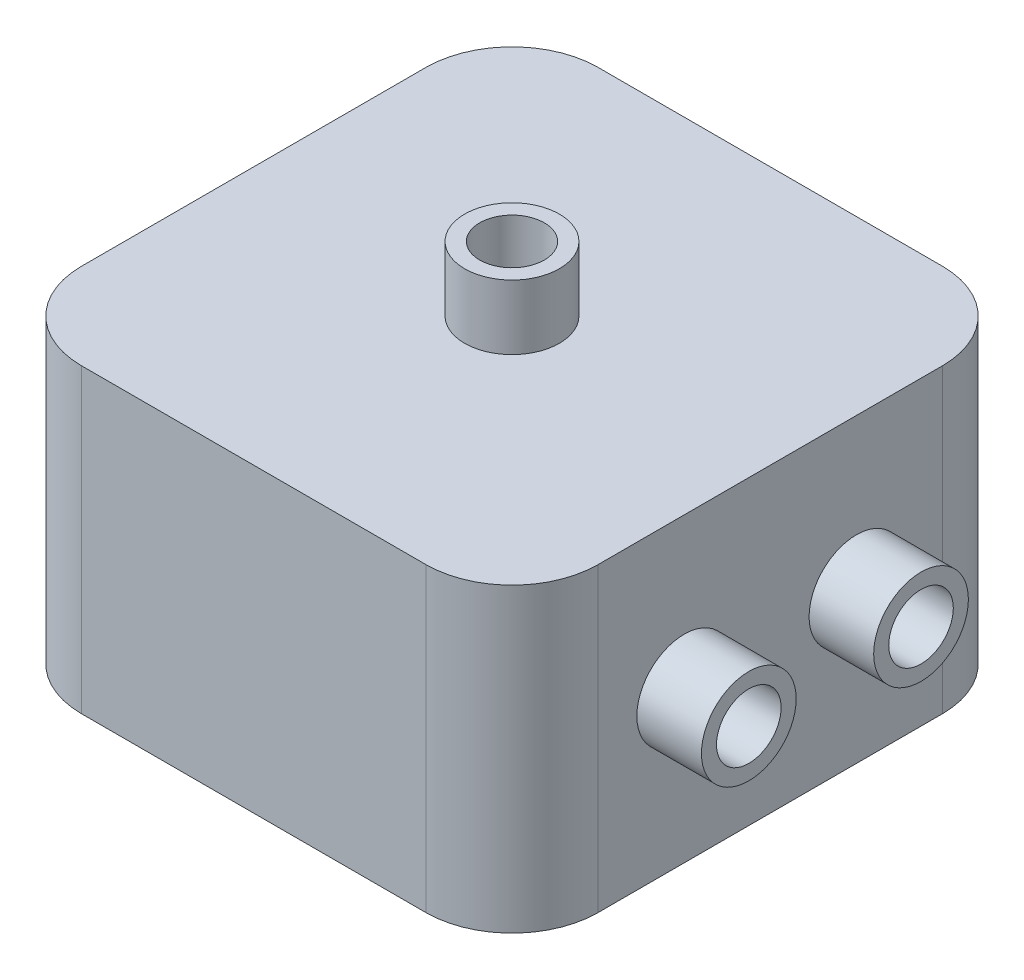
SolidWorks part; units mm, degrees
other "Câmera1"
material "PET"
ref_plane "Plano frontal" through (0, 0, 0) normal (0, 0, 1) x (1, 0, 0)
ref_plane "Plano superior" through (0, 0, 0) normal (0, 1, 0) x (1, 0, 0)
ref_plane "Plano direito" through (0, 0, 0) normal (1, 0, 0) x (0, 0, -1)
sketch "Esboço1" plane through (0, 0, 0) normal (0, 1, 0) x (1, 0, 0)
  line L0 (40, 60) -> (-40, 60)
  line L1 (40, -50) -> (-40, -50)
  line L2 (50, -40) -> (50, 40)
  line L3 (40, 50) -> (-40, 50)
  line L4 (-50, -40) -> (-50, 40)
  line L5 (50, -50) -> (-50, 50) construction
  line L6 (50, 50) -> (-50, -50) construction
  line L7 (-60, -40) -> (-60, 40)
  line L8 (40, -60) -> (-40, -60)
  line L9 (60, -40) -> (60, 40)
  arc A0 (-40, -50) -> (-50, -40) centre (-40, -40) cw
  arc A1 (50, -40) -> (40, -50) centre (40, -40) cw
  arc A2 (50, 40) -> (40, 50) centre (40, 40) ccw
  arc A3 (-40, 50) -> (-50, 40) centre (-40, 40) ccw
  arc A4 (-40, 60) -> (-60, 40) centre (-40, 40) ccw
  arc A5 (-40, -60) -> (-60, -40) centre (-40, -40) cw
  arc A6 (60, -40) -> (40, -60) centre (40, -40) cw
  arc A7 (60, 40) -> (40, 60) centre (40, 40) ccw
  point P0 (0, 0)
  dimension "D3" = 10
  dimension "D1" = 100
  dimension "D2" = 100
  dimension "D4" = 10
extrude "Ressalto-extrusão1" add sketch "Esboço1" along normal blind 50
ref_plane "Plano1" through (0, 50, 0) normal (0, 1, 0) x (1, 0, 0)
sketch "Esboço2" plane through (0, 50, 0) normal (0, 1, 0) x (1, 0, 0)
  line L0 (-40, -50) -> (40, -50) construction
  line L1 (-40, 50) -> (40, 50) construction
  line L2 (-50, 40) -> (-50, -40) construction
  line L3 (-40, -50) -> (40, -50) construction
  line L4 (50, 40) -> (50, -40) construction
  line L5 (-50, 50) -> (50, -50) construction
  line L6 (-50, -50) -> (50, 50) construction
  line L7 (50, -40) -> (50, 40) construction
  line L8 (-40, -60) -> (40, -60)
  line L9 (60, 40) -> (60, -40)
  line L10 (-40, 60) -> (40, 60)
  line L11 (-60, 40) -> (-60, -40)
  arc A0 (-50, -40) -> (-40, -50) centre (-40, -40) ccw construction
  arc A1 (40, 50) -> (50, 40) centre (40, 40) cw construction
  arc A2 (-40, 50) -> (-50, 40) centre (-40, 40) ccw construction
  arc A3 (40, -50) -> (50, -40) centre (40, -40) ccw construction
  arc A4 (40, -60) -> (60, -40) centre (40, -40) ccw
  arc A5 (40, 60) -> (60, 40) centre (40, 40) cw
  arc A6 (-40, 60) -> (-60, 40) centre (-40, 40) ccw
  arc A7 (-60, -40) -> (-40, -60) centre (-40, -40) ccw
  point P0 (0, 0)
  dimension "D1" = 10
  dimension "D2" = 10
extrude "Ressalto-extrusão2" add sketch "Esboço2" along normal blind 10
ref_plane "Plano2" through (0, 0, 0) normal (0, -1, 0) x (-1, 0, 0)
sketch "Esboço3" plane through (0, 0, 0) normal (0, -1, 0) x (-1, 0, 0)
  line L0 (40, -50) -> (-40, -50) construction
  line L1 (40, 50) -> (-40, 50) construction
  line L2 (50, 40) -> (50, -40) construction
  line L3 (40, -50) -> (-40, -50) construction
  line L4 (-50, 40) -> (-50, -40) construction
  line L5 (50, 50) -> (-50, -50) construction
  line L6 (50, -50) -> (-50, 50) construction
  line L7 (-50, -40) -> (-50, 40) construction
  line L8 (40, -60) -> (-40, -60)
  line L9 (-60, 40) -> (-60, -40)
  line L10 (40, 60) -> (-40, 60)
  line L11 (60, 40) -> (60, -40)
  arc A0 (-50, -40) -> (-40, -50) centre (-40, -40) ccw construction
  arc A1 (-40, 50) -> (-50, 40) centre (-40, 40) ccw construction
  arc A2 (50, 40) -> (40, 50) centre (40, 40) ccw construction
  arc A3 (40, -50) -> (50, -40) centre (40, -40) ccw construction
  arc A4 (-60, -40) -> (-40, -60) centre (-40, -40) ccw
  arc A5 (-40, 60) -> (-60, 40) centre (-40, 40) ccw
  arc A6 (60, 40) -> (40, 60) centre (40, 40) ccw
  arc A7 (40, -60) -> (60, -40) centre (40, -40) ccw
  point P0 (0, 0)
  dimension "D1" = 10
  dimension "D2" = 10
extrude "Ressalto-extrusão3" add sketch "Esboço3" along normal blind 10
ref_plane "Plano3" through (-60, 0, 0) normal (-1, 0, 0) x (0, 0, 1)
sketch "Esboço4" plane through (-60, 0, 0) normal (-1, 0, 0) x (0, 0, 1)
  line L0 (0, 60) -> (0, -10) construction
  line L1 (-40, 60) -> (40, 60) construction
  line L2 (40, -10) -> (-40, -10) construction
  line L3 (-40, 25) -> (40, 25) construction
  line L4 (-40, 60) -> (-40, -10) construction
  line L5 (40, 60) -> (40, -10) construction
  line L6 (0, 25) -> (40, 25) construction
  circle A0 centre (20, 25) radius 11
  circle A1 centre (-20, 25) radius 11
extrude "Ressalto-extrusão4" add sketch "Esboço4" along normal blind 15
ref_plane "Plano4" through (60, 0, 0) normal (1, 0, 0) x (0, 0, -1)
sketch "Esboço5" plane through (60, 0, 0) normal (1, 0, 0) x (0, 0, -1)
  line L0 (0, 0) -> (0, 60) construction
  line L1 (-40, 60) -> (40, 60) construction
  line L2 (40, 25) -> (0, 25) construction
  line L3 (40, 60) -> (40, -10) construction
  line L4 (0, 25) -> (-40, 25) construction
  line L5 (-40, 60) -> (-40, -10) construction
  circle A0 centre (-20, 25) radius 11
  circle A1 centre (20, 25) radius 11
extrude "Ressalto-extrusão5" add sketch "Esboço5" along normal blind 15
ref_plane "Plano5" through (-75, 0, 0) normal (-1, 0, 0) x (0, 0, 1)
sketch "Esboço6" plane through (-75, 0, 0) normal (-1, 0, 0) x (0, 0, 1)
  circle A0 centre (20, 25) radius 7.5
  circle A1 centre (-20, 25) radius 7.5
extrude "Corte-extrusão1" cut sketch "Esboço6" against normal blind 200
ref_plane "Plano6" through (0, 60, 0) normal (0, 1, 0) x (1, 0, 0)
sketch "Esboço7" plane through (0, 60, 0) normal (0, 1, 0) x (1, 0, 0)
  circle A0 centre (0, 0) radius 11
extrude "Ressalto-extrusão6" add sketch "Esboço7" along normal blind 15
ref_plane "Plano7" through (0, 75, 0) normal (0, 1, 0) x (1, 0, 0)
sketch "Esboço8" plane through (0, 75, 0) normal (0, 1, 0) x (1, 0, 0)
  circle A0 centre (0, 0) radius 7.5
extrude "Corte-extrusão2" cut sketch "Esboço8" against normal blind 30
